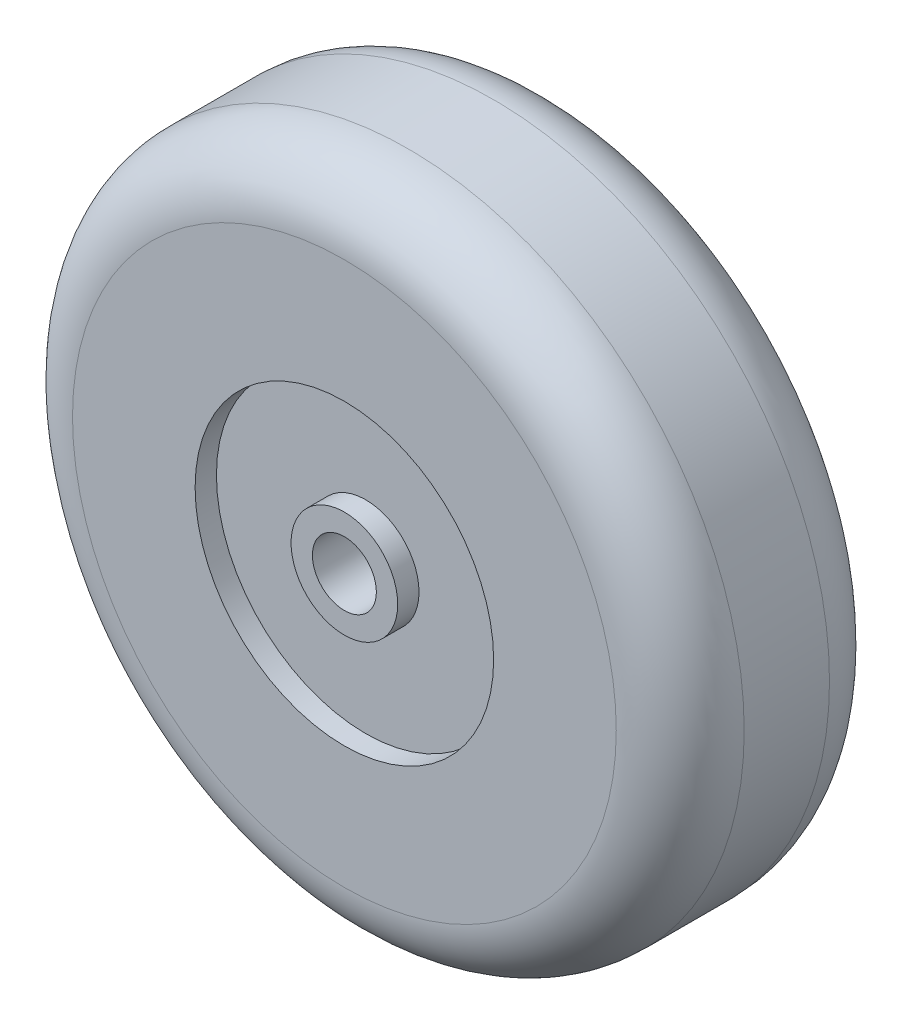
SolidWorks part; units mm, degrees
ref_plane "Front Plane" through (0, 0, 0) normal (0, 0, 1) x (1, 0, 0)
ref_plane "Top Plane" through (0, 0, 0) normal (0, 1, 0) x (1, 0, 0)
ref_plane "Right Plane" through (0, 0, 0) normal (1, 0, 0) x (0, 0, -1)
sketch "Sketch1" plane through (0, 0, 0) normal (0, 0, 1) x (1, 0, 0)
  line L0 (-12.5, -65.6639) -> (-79.4547, -65.6639) construction
  circle A1 centre (-62.5, -49.9139) radius 15.75
  circle A2 centre (-62.5, -49.9139) radius 1.5
  dimension "D1" = 31.5
extrude "Boss-Extrude1" add sketch "Sketch1" along normal blind 10
sketch "Sketch2" plane through (0, 0, 10) normal (0, 0, 1) x (1, 0, 0)
  circle A0 centre (-62.5, -49.9139) radius 2.5
  circle A1 centre (-62.5, -49.9139) radius 7
  dimension "D1" = 14
  dimension "D2" = 5
extrude "Cut-Extrude1" cut sketch "Sketch2" against normal blind 1
sketch "Sketch3" plane through (0, 0, 0) normal (0, 0, -1) x (-1, 0, 0)
  circle A0 centre (62.5, -49.9139) radius 2.5 construction
  circle A1 centre (62.5, -49.9139) radius 7
  circle A2 centre (62.5, -49.9139) radius 7
  circle A3 centre (62.5, -49.9139) radius 2.5
  dimension "D1" = 0
extrude "Cut-Extrude2" cut sketch "Sketch3" against normal blind 1
fillet "Fillet1" radius 3 2 edges at (-46.75, -49.9139, 10) (-46.75, -49.9139, 0)
